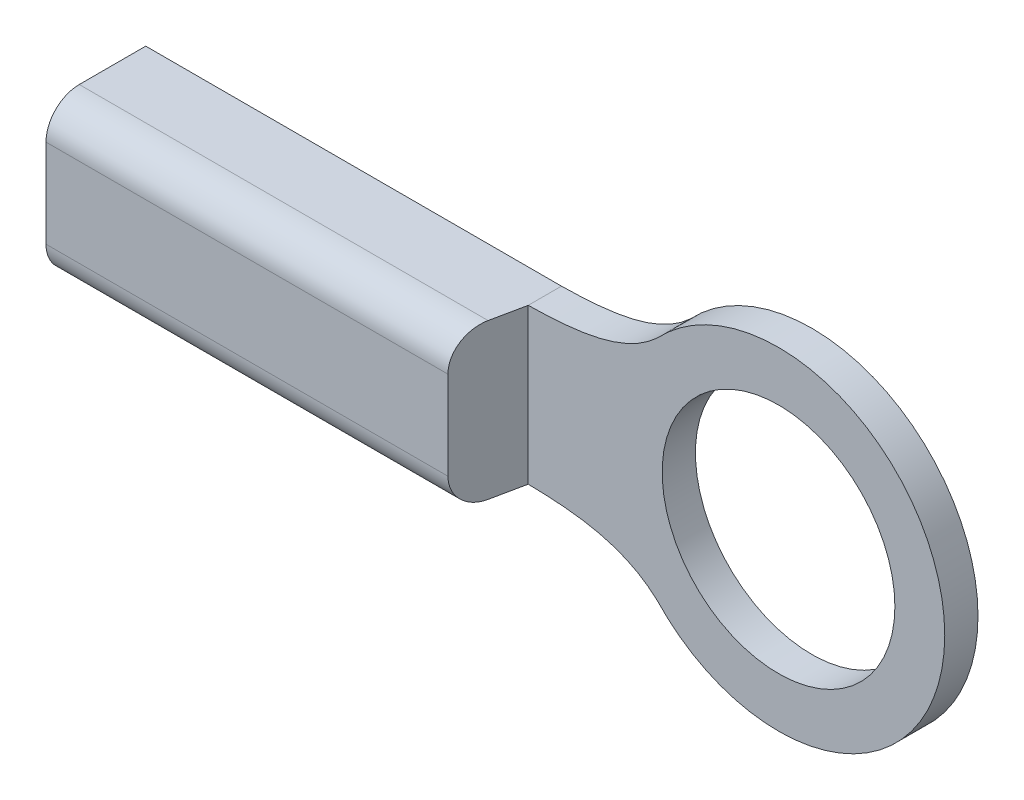
SolidWorks part; units mm, degrees
ref_plane "正面" through (0, 0, 0) normal (0, 0, 1) x (1, 0, 0)
ref_plane "平面" through (0, 0, 0) normal (0, 1, 0) x (1, 0, 0)
ref_plane "右側面" through (0, 0, 0) normal (1, 0, 0) x (0, 0, -1)
sketch "ｽｹｯﾁ1" plane through (0, 0, 0) normal (0, 0, 1) x (1, 0, 0)
  line L0 (0, 0) -> (6.4107, 0) construction
  line L1 (-2.6355, 1.4234) -> (-11.1355, 1.4234)
  line L2 (-2.6355, -1.4234) -> (-11.1355, -1.4234)
  line L3 (-11.1355, 1.4234) -> (-11.1355, -1.4234)
  circle A0 centre (0, 0) radius 1.75
  circle A1 centre (0, 0) radius 2.5
  spline S0 degree 2 poles (-1.86, 1.6704) (-2.2002, 1.4101) (-2.6355, 1.4234) knots 0 0 0 1 1 1
  spline S1 degree 2 poles (-1.86, -1.6704) (-2.2002, -1.4101) (-2.6355, -1.4234) knots 0 0 0 1 1 1
  dimension "D1" = 3.5
  dimension "D2" = 5
  dimension "D3" = 8.5
extrude "ﾎﾞｽ - 押し出し1" add sketch "ｽｹｯﾁ1" along normal blind 0.5 contours A1 L0 A0 | L0 A1 A0 | S0 L1 L3 L2 S1
sketch "ｽｹｯﾁ2" plane through (0, 0, 0) normal (0, 0, 1) x (1, 0, 0)
  line L0 (0, 0) -> (-3.9698, 0) construction
  line L1 (-3.7648, 1.1648) -> (-10.0172, 1.1648)
  line L2 (-3.7648, -1.1648) -> (-10.0172, -1.1648)
  line L3 (-10.0172, 1.1648) -> (-10.0172, -1.1648)
  circle A0 centre (0, 0) radius 2.5 construction
  circle A1 centre (0, 0) radius 2.5
  spline S0 degree 3 poles (-1.8242, 1.7094) (-2.3418, 1.2283) (-3.0985, 1.179) (-3.7648, 1.1648) knots 0 0 0 0 1 1 1 1
  spline S1 degree 3 poles (-1.8242, -1.7094) (-2.3418, -1.2283) (-3.0985, -1.179) (-3.7648, -1.1648) knots 0 0 0 0 1 1 1 1
  dimension "D1" = 5
extrude "ﾎﾞｽ - 押し出し2" add sketch "ｽｹｯﾁ2" along normal blind 1.5 contours L0 A1 S0 L1 L3 | A1 L0 L3 L2 S1
sketch "ｽｹｯﾁ3" plane through (0, 0, 0) normal (0, 1, 0) x (1, 0, 0)
  line L0 (-3.9869, -1.5732) -> (-3.7648, -0.5)
  line L1 (-3.7648, -1.5) -> (-3.7648, 0) construction
  line L2 (-3.7648, -0.5) -> (-1.8242, -0.5)
  line L3 (-1.8242, -0.5) -> (-1.8242, -1.9217)
  line L4 (-1.8242, -1.9217) -> (-3.9869, -1.9217)
  line L5 (-3.9869, -1.9217) -> (-3.9869, -1.5732)
extrude "ｶｯﾄ - 押し出し1" cut sketch "ｽｹｯﾁ3" against normal through all both and the other way through all
fillet "ﾌｨﾚｯﾄ1" radius 0.5 2 edges at (-6.9945, 1.1648, 1.5) (-6.9945, -1.1648, 1.5)
sketch "ｽｹｯﾁ4" plane through (-10.0172, 0, 0) normal (-1, 0, 0) x (0, 0, 1)
  circle A0 centre (0.7932, 0) radius 0.5575
  point P2 (0, 0)
  point P3 (0.7932, 0)
extrude "ｶｯﾄ - 押し出し2" cut sketch "ｽｹｯﾁ4" against normal blind 0.1
